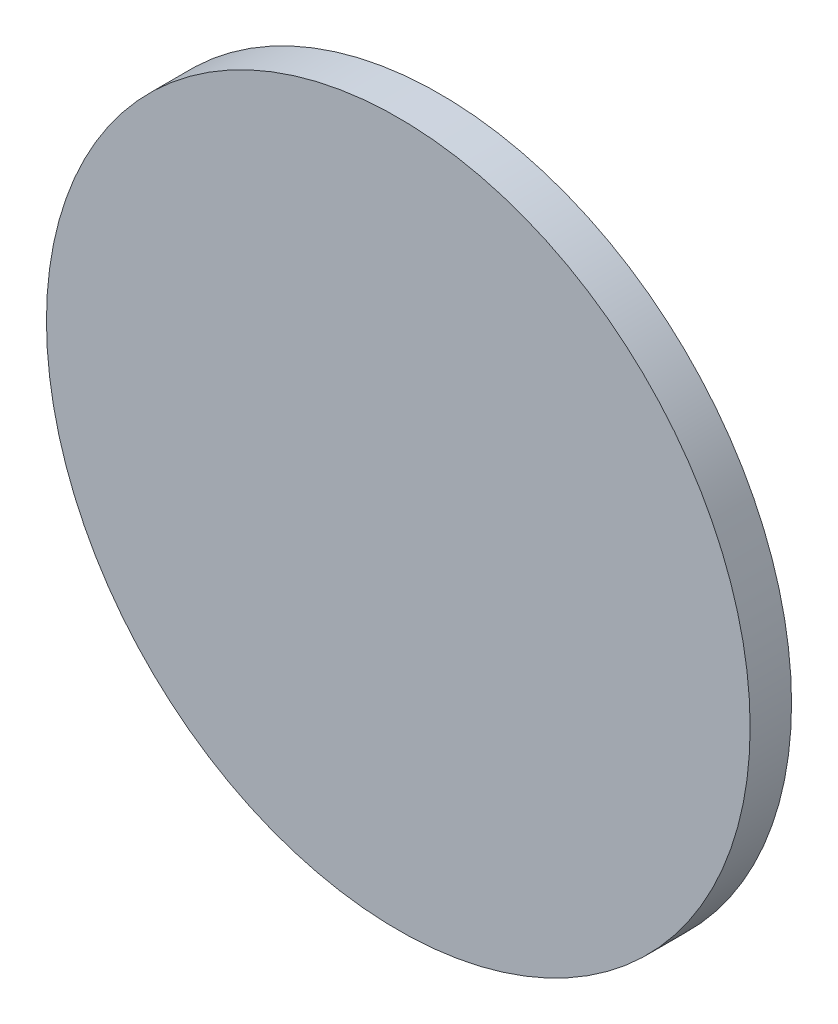
SolidWorks part; units mm, degrees
ref_plane "Plan de face" through (0, 0, 0) normal (0, 0, 1) x (1, 0, 0)
ref_plane "Plan de dessus" through (0, 0, 0) normal (0, 1, 0) x (1, 0, 0)
ref_plane "Plan de droite" through (0, 0, 0) normal (1, 0, 0) x (0, 0, -1)
sketch "Esquisse1" plane through (0, 0, 0) normal (0, 0, 1) x (1, 0, 0)
  circle A0 centre (0, 0) radius 42.5
  dimension "D1" = 85
extrude "Boss.-Extru.1" add sketch "Esquisse1" along normal blind 5
